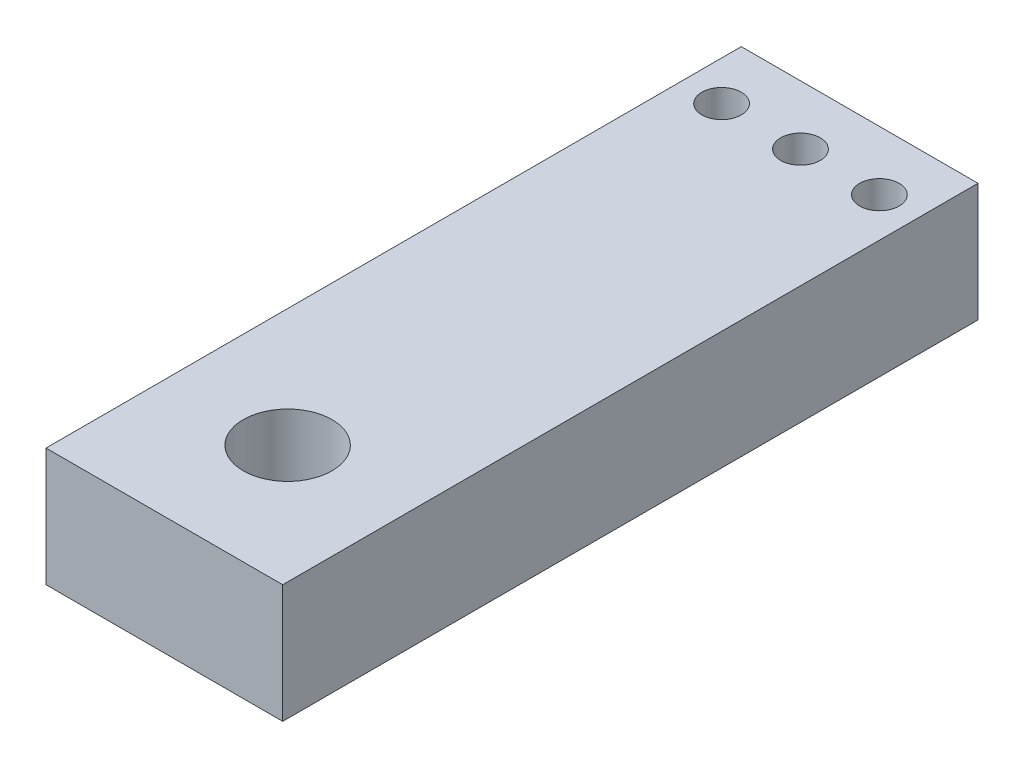
SolidWorks part; units mm, degrees
ref_plane "Front Plane" through (0, 0, 0) normal (0, 0, 1) x (1, 0, 0)
ref_plane "Top Plane" through (0, 0, 0) normal (0, 1, 0) x (1, 0, 0)
ref_plane "Right Plane" through (0, 0, 0) normal (1, 0, 0) x (0, 0, -1)
sketch "Sketch1" plane through (0, 0, 0) normal (0, 1, 0) x (1, 0, 0)
  line L1 (0, 0) -> (12, 0)
  line L2 (0, 0) -> (0, 35.25)
  line L3 (0, 35.25) -> (12, 35.25)
  line L4 (12, 0) -> (12, 35.25)
  dimension "D1" = 35.25
  dimension "D2" = 12
extrude "Boss-Extrude1" add sketch "Sketch1" along normal blind 6
sketch "Sketch2" plane through (0, 6, 0) normal (0, 1, 0) x (1, 0, 0)
  line L0 (0, 0) -> (12, 0) construction
  line L1 (12, 35.25) -> (0, 35.25) construction
  line L2 (0, 35.25) -> (0, 0) construction
  line L4 (12, 0) -> (12, 35.25) construction
  circle A0 centre (10, 32.25) radius 1
  circle A1 centre (6, 6.25) radius 2.25
  circle A2 centre (2, 32.25) radius 1
  circle A3 centre (6, 32.25) radius 1
  point P8 (6, 0)
  dimension "D1" = 4.5
  dimension "D2" = 2
  dimension "D3" = 6.25
  dimension "D4" = 3
  dimension "D5" = 2
  dimension "D6" = 2
extrude "Cut-Extrude1" cut sketch "Sketch2" against normal through all
